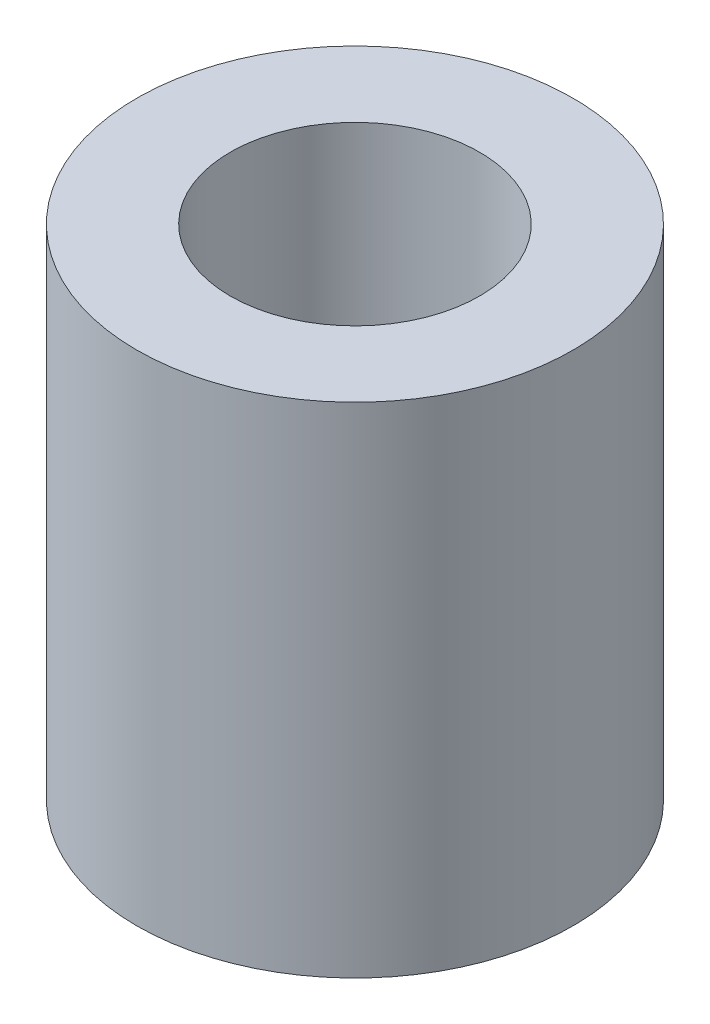
SolidWorks part; units mm, degrees
ref_plane "Спереди" through (0, 0, 0) normal (0, 0, 1) x (1, 0, 0)
ref_plane "Сверху" through (0, 0, 0) normal (0, 1, 0) x (1, 0, 0)
ref_plane "Справа" through (0, 0, 0) normal (1, 0, 0) x (0, 0, -1)
sketch "Эскиз1" plane through (0, 0, 0) normal (0, 1, 0) x (1, 0, 0)
  circle A0 centre (0, 0) radius 2
  circle A1 centre (0, 0) radius 3.5
  dimension "D1" = 4
  dimension "D2" = 7
extrude "Бобышка-Вытянуть1" add sketch "Эскиз1" along normal blind 8
